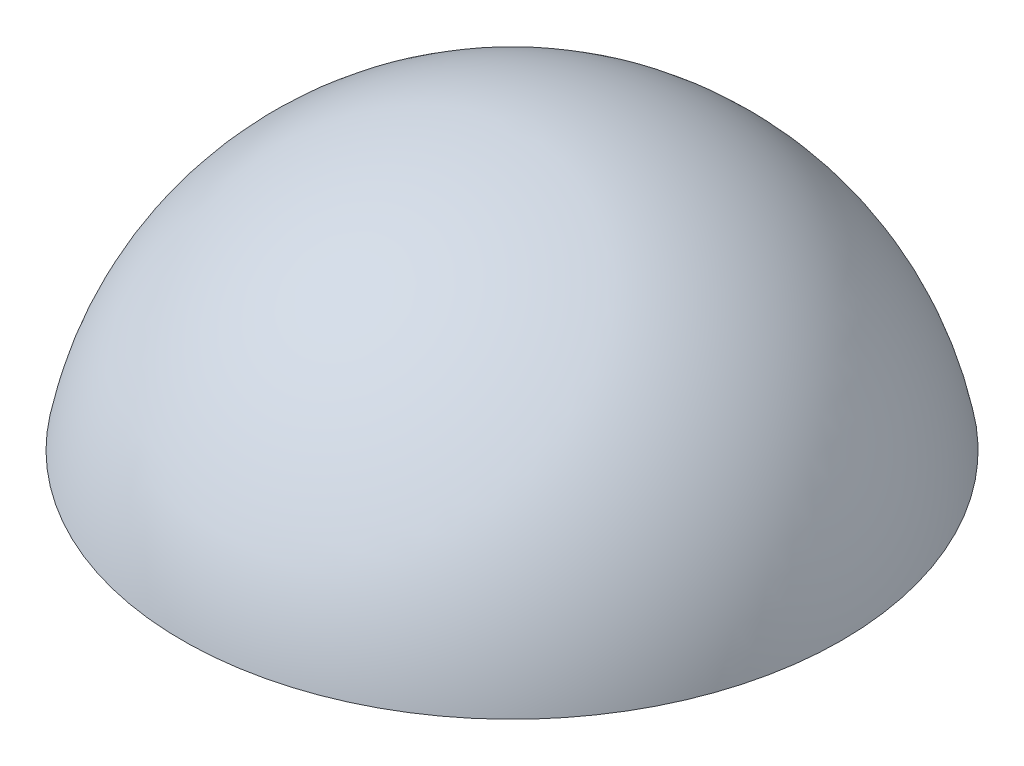
SolidWorks part; units mm, degrees
ref_plane "Front Plane" through (0, 0, 0) normal (0, 0, 1) x (1, 0, 0)
ref_plane "Top Plane" through (0, 0, 0) normal (0, 1, 0) x (1, 0, 0)
ref_plane "Right Plane" through (0, 0, 0) normal (1, 0, 0) x (0, 0, -1)
sketch "Sketch2" plane through (0, 0, 0) normal (0, 0, 1) x (1, 0, 0)
  line L0 (0, 762) -> (0, 152.4)
  line L1 (0, 152.4) -> (746.6045, 152.4)
  arc A0 (0, 762) -> (746.6045, 152.4) centre (0, 0) cw
  dimension "D1" = 762
  dimension "D2" = 609.6
revolve "Revolve1" add sketch "Sketch2" angle 360 about L0
shell "Shell1" thickness 76.2
sketch "Sketch3" plane through (0, 0, 0) normal (1, 0, 0) x (0, 0, -1)
  circle A0 centre (0, 0) radius 254
  dimension "D1" = 508
extrude "Cut-Extrude1" cut sketch "Sketch3" against normal up to next
